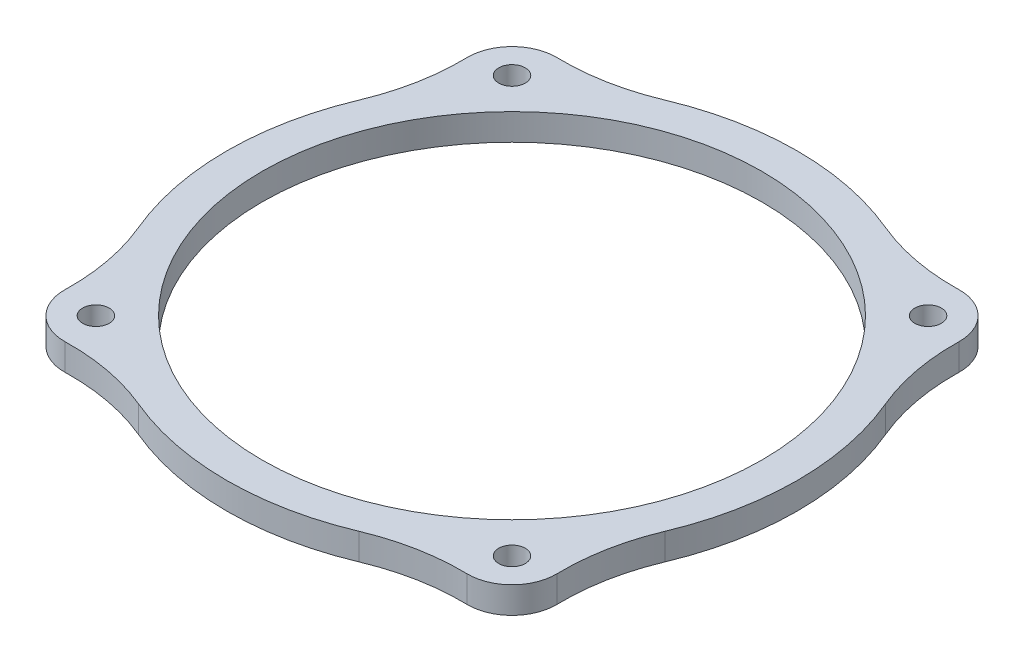
SolidWorks part; units mm, degrees
ref_plane "Front Plane" through (0, 0, 0) normal (0, 0, 1) x (1, 0, 0)
ref_plane "Top Plane" through (0, 0, 0) normal (0, 1, 0) x (1, 0, 0)
ref_plane "Right Plane" through (0, 0, 0) normal (1, 0, 0) x (0, 0, -1)
sketch "Sketch1" plane through (0, 0, 0) normal (0, 1, 0) x (1, 0, 0)
  line L0 (-39.8881, 0) -> (39.8881, 0) construction
  line L1 (0, 0) -> (0, 33) construction
  line L2 (0, 0) -> (23.5113, 23.5113) construction
  circle A0 centre (0, 0) radius 28.25
  circle A1 centre (0, 0) radius 32.25 construction
  arc A2 (-19.0052, 26.055) -> (19.0052, 26.055) centre (0, 0) cw
  arc A3 (19.0052, 26.055) -> (26.055, 19.0052) centre (22.8042, 22.8042) cw
  arc A4 (26.055, 19.0052) -> (26.055, -19.0052) centre (0, 0) cw
  circle A5 centre (23.5113, 23.5113) radius 1.5
  arc A6 (-26.055, 19.0052) -> (-26.055, -19.0052) centre (0, 0) ccw
  circle A7 centre (23.5113, -23.5113) radius 1.5
  arc A8 (-19.0052, 26.055) -> (-26.055, 19.0052) centre (-22.8042, 22.8042) ccw
  circle A9 centre (-23.5113, -23.5113) radius 1.5
  arc A10 (19.0052, -26.055) -> (26.055, -19.0052) centre (22.8042, -22.8042) ccw
  arc A11 (-19.0052, -26.055) -> (19.0052, -26.055) centre (0, 0) ccw
  circle A12 centre (-23.5113, 23.5113) radius 1.5
  arc A13 (-19.0052, -26.055) -> (-26.055, -19.0052) centre (-22.8042, -22.8042) cw
  point P30 (0, 0)
  dimension "D1" = 56.5
  dimension "D2" = 4
  dimension "D3" = 5
  dimension "D5" = 45
  dimension "D6" = 3
  dimension "D4" = 1
  dimension "D7" = 4
extrude "Boss-Extrude1" add sketch "Sketch1" along normal blind 3
fillet "Fillet1" radius 25 8 edges at (-26.055, 1.5, 19.0052) (-26.055, 1.5, -19.0052) (-19.0052, 1.5, -26.055) (19.0052, 1.5, -26.055) (26.055, 1.5, -19.0052) (26.055, 1.5, 19.0052) (19.0052, 1.5, 26.055) (-19.0052, 1.5, 26.055)
